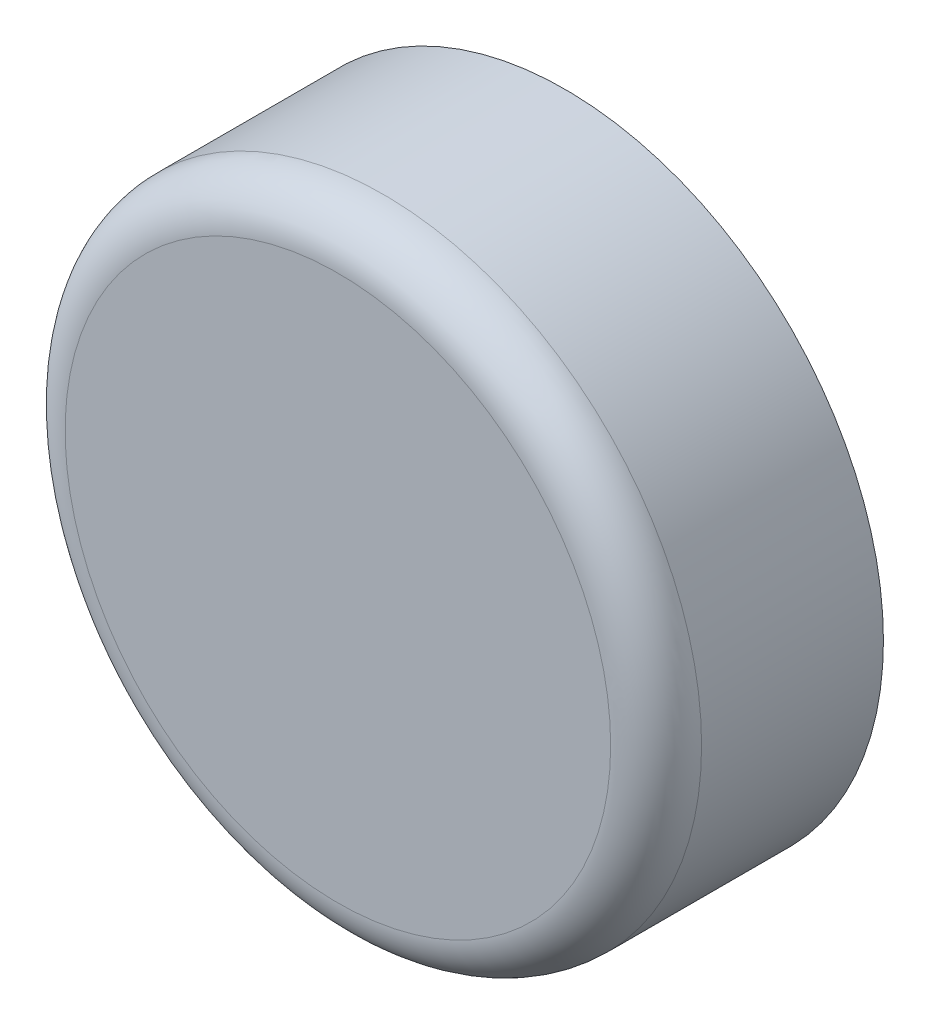
SolidWorks part; units mm, degrees
material "Glas"
ref_plane "Ebene vorne" through (0, 0, 0) normal (0, 0, 1) x (1, 0, 0)
ref_plane "Ebene oben" through (0, 0, 0) normal (0, 1, 0) x (1, 0, 0)
ref_plane "Ebene rechts" through (0, 0, 0) normal (1, 0, 0) x (0, 0, -1)
sketch "Skizze1" plane through (0, 0, 0) normal (0, 0, 1) x (1, 0, 0)
  circle A0 centre (0, 0) radius 14
  dimension "D1" = 28
extrude "Aufsatz-Linear austragen1" add sketch "Skizze1" along normal blind 10
fillet "Verrundung1" radius 2 1 edges at (14, 0, 10)
